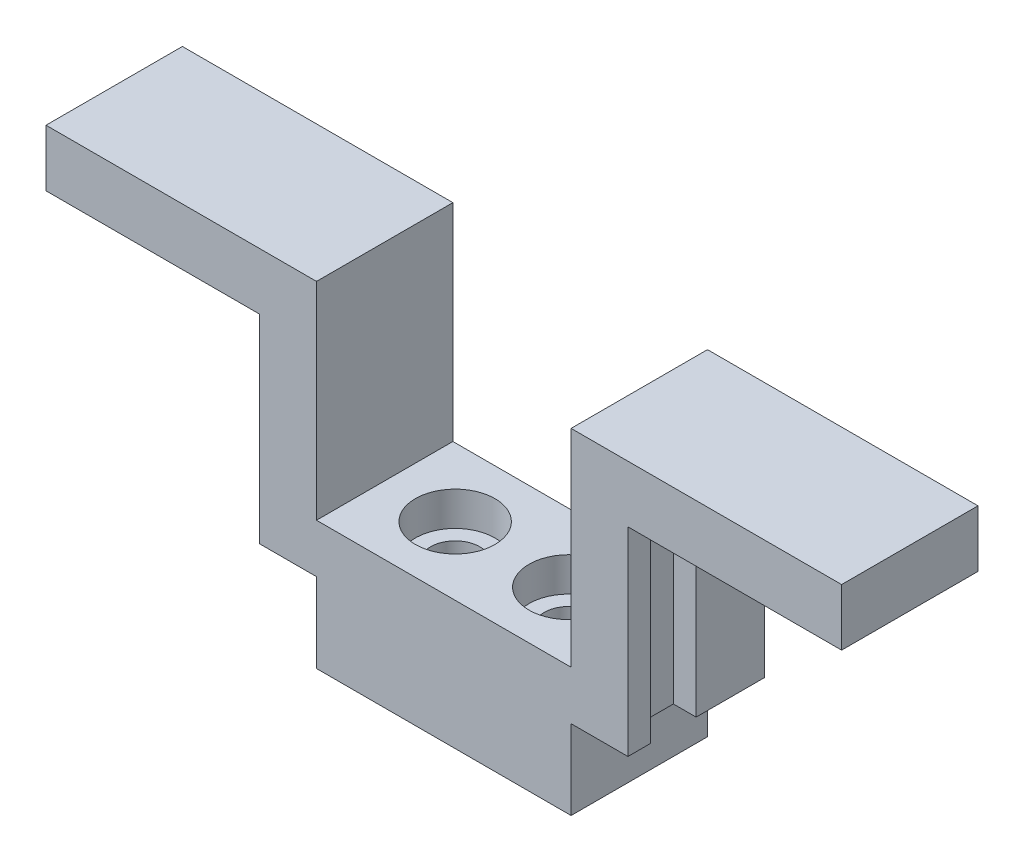
SolidWorks part; units mm, degrees
ref_plane "Front Plane" through (0, 0, 0) normal (0, 0, 1) x (1, 0, 0)
ref_plane "Top Plane" through (0, 0, 0) normal (0, 1, 0) x (1, 0, 0)
ref_plane "Right Plane" through (0, 0, 0) normal (1, 0, 0) x (0, 0, -1)
sketch "Sketch2" plane through (0, 0, 0) normal (0, 0, 1) x (1, 0, 0)
  line L1 (0, 0) -> (5, 0)
  line L2 (0, 0) -> (0, 17.5)
  line L4 (5, 0) -> (5, 17.5)
  line L5 (5, 17.5) -> (23.8, 17.5)
  line L6 (0, 17.5) -> (0, 22.5)
  line L7 (0, 22.5) -> (23.8, 22.5)
  line L8 (23.8, 17.5) -> (23.8, 22.5)
  dimension "D1" = 17.5
  dimension "D2" = 5
  dimension "D3" = 5
  dimension "D4" = 23.8
extrude "Boss-Extrude2" add sketch "Sketch2" along normal blind 12
sketch "Sketch3" plane through (5, 0, 0) normal (1, 0, 0) x (0, 0, -1)
  line L0 (-12, 0) -> (0, 0) construction
  line L1 (-10, 17.5) -> (-6, 17.5)
  line L2 (-10, 17.5) -> (-10, 0)
  line L3 (-10, 0) -> (-6, 0)
  line L4 (-6, 17.5) -> (-6, 0)
  line L5 (-12, 0) -> (-12, 17.5) construction
  dimension "D1" = 4
extrude "Cut-Extrude1" cut sketch "Sketch3" against normal blind 2
sketch "Sketch4" plane through (0, 0, 0) normal (-1, 0, 0) x (0, 0, 1)
  line L0 (0, 22.5) -> (0, 0) construction
  line L1 (0, 4.3) -> (12, 4.3)
  line L2 (0, 4.3) -> (0, -7)
  line L3 (0, -7) -> (12, -7)
  line L4 (12, 4.3) -> (12, -7)
  line L5 (12, 22.5) -> (12, 0) construction
  line L6 (12, 0) -> (0, 0) construction
  dimension "D1" = 4.3
  dimension "D2" = 7
extrude "Boss-Extrude3" add sketch "Sketch4" along normal blind 11.2
ref_plane "Plane1" through (-11.2, 0, 0) normal (-1, 0, 0) x (0, 0, 1)
mirror "Mirror4" about plane through (-11.2, 0, 0) normal (-1, 0, 0) of "Boss-Extrude3"
mirror "Mirror5" about plane through (-11.2, 0, 0) normal (-1, 0, 0) of "Boss-Extrude2"
mirror "Mirror6" about plane through (-11.2, 0, 0) normal (-1, 0, 0) of "Cut-Extrude1"
sketch "Sketch5" plane through (0, 4.3, 0) normal (0, 1, 0) x (1, 0, 0)
  line L0 (-16.2, -6) -> (-16.2, 0) construction
  line L1 (-22.4, 0) -> (0, 0) construction
  line L2 (-16.2, -6) -> (-16.2, -12) construction
  line L3 (-22.4, -12) -> (0, -12) construction
  line L4 (-22.4, -6) -> (-16.2, -6) construction
  line L5 (-22.4, -12) -> (-22.4, 0) construction
  line L6 (-6.2, -6) -> (0, -6) construction
  line L7 (0, -12) -> (0, 0) construction
  circle A0 centre (-16.2, -6) radius 3.5
  circle A1 centre (-6.2, -6) radius 3.5
  dimension "D2" = 7
  dimension "D1" = 10
extrude "Cut-Extrude2" cut sketch "Sketch5" against normal blind 3
sketch "Sketch6" plane through (0, 1.3, 0) normal (0, 1, 0) x (1, 0, 0)
  circle A0 centre (-16.2, -6) radius 2.165
  circle A1 centre (-6.2, -6) radius 2.165
  dimension "D1" = 4.33
extrude "Cut-Extrude3" cut sketch "Sketch6" against normal through all
